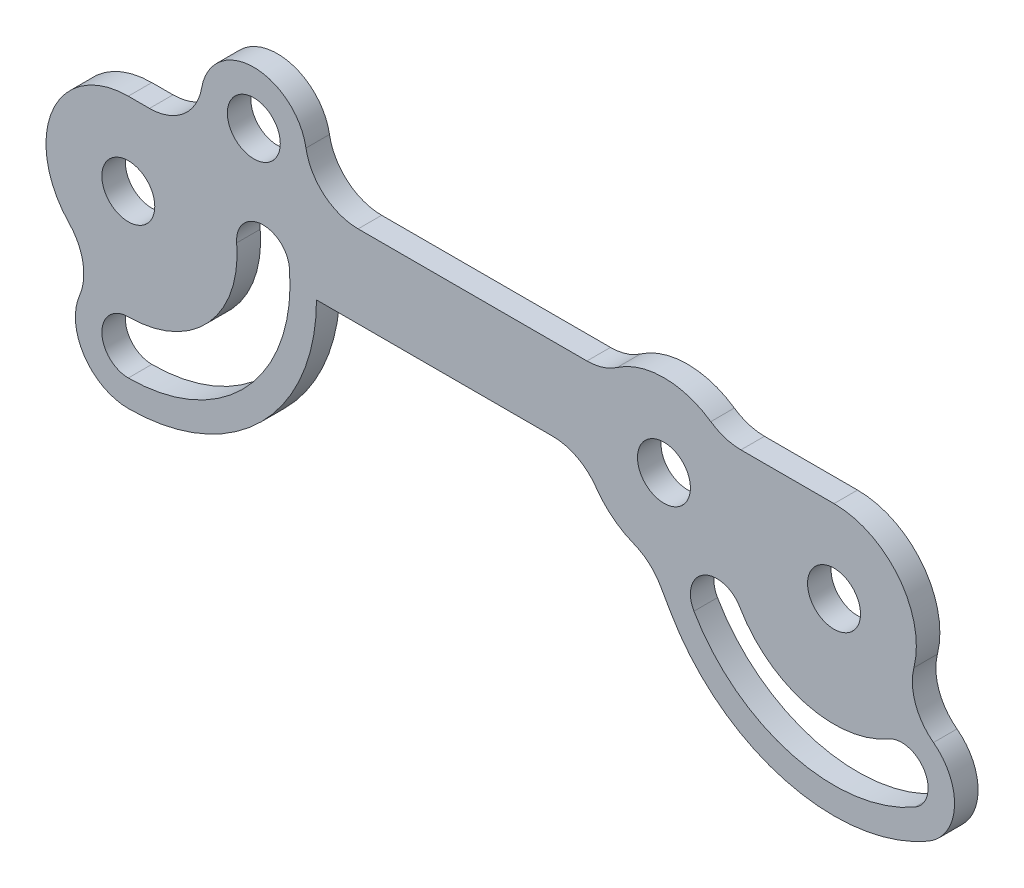
SolidWorks part; units mm, degrees
ref_plane "Front Plane" through (0, 0, 0) normal (0, 0, 1) x (1, 0, 0)
ref_plane "Top Plane" through (0, 0, 0) normal (0, 1, 0) x (1, 0, 0)
ref_plane "Right Plane" through (0, 0, 0) normal (1, 0, 0) x (0, 0, -1)
sketch "Sketch1" plane through (0, 0, 0) normal (0, 0, 1) x (1, 0, 0)
  line L0 (5.5562, 0) -> (42.0688, 0)
  line L1 (0, 5.5562) -> (47.625, 5.5562)
  line L2 (0, 5.5562) -> (0, -5.5562) construction
  line L3 (0, -5.5562) -> (47.625, -5.5562) construction
  line L4 (47.625, 5.5562) -> (47.625, -5.5562) construction
  line L5 (0, 5.5562) -> (47.625, 5.5562) construction
  line L9 (36.6265, -6.35) -> (33.0546, -0.1633)
  line L10 (36.6265, -6.35) -> (39.7198, -4.5641) construction
  line L11 (0, 0) -> (9.0934, 0.7956) construction
  line L12 (9.0934, 0.7956) -> (8.4708, 7.9121) construction
  line L13 (47.625, 0) -> (52.1891, -7.9052) construction
  line L14 (52.1891, -7.9052) -> (53.082, -9.4519) construction
  line L15 (47.625, 0) -> (47.625, -9.1281) construction
  line L16 (47.625, 0) -> (39.7198, -4.5641) construction
  line L17 (39.7198, -4.5641) -> (36.1479, 1.6226) construction
  line L18 (33.0546, -0.1633) -> (32.9603, 0)
  circle A0 centre (0, 0) radius 5.5562 construction
  circle A1 centre (47.625, 0) radius 5.5562 construction
  arc A2 (0, 5.5562) -> (0, -5.5562) centre (0, 0) ccw
  arc A3 (47.625, -5.5562) -> (47.625, 5.5562) centre (47.625, 0) ccw
  circle A4 centre (0, 0) radius 1.7859
  circle A5 centre (47.625, 0) radius 1.7859
  arc A6 (0, -5.5562) -> (5.5562, 0) centre (0, 0) ccw
  arc A7 (42.0688, 0) -> (47.625, -5.5562) centre (47.625, 0) ccw
  circle A16 centre (0, -9.1281) radius 1.7859
  circle A20 centre (0, -9.1281) radius 3.5719
  circle A21 centre (9.0934, 0.7956) radius 1.7859
  circle A22 centre (9.0934, 0.7956) radius 3.5719 construction
  circle A23 centre (47.625, 0) radius 9.1281 construction
  circle A25 centre (0, 0) radius 9.1281 construction
  circle A40 centre (8.4708, 7.9121) radius 1.7859
  circle A41 centre (8.4708, 7.9121) radius 3.5719
  circle A42 centre (39.7198, -4.5641) radius 3.5719
  circle A44 centre (36.1479, 1.6226) radius 3.5719 construction
  circle A46 centre (36.1479, 1.6226) radius 1.7859
  circle A47 centre (39.7198, -4.5641) radius 1.7859
  circle A49 centre (52.1891, -7.9052) radius 3.5719
  circle A50 centre (52.1891, -7.9052) radius 1.7859
  arc A51 (51.2961, -6.3585) -> (41.2665, -3.6711) centre (47.625, 0) cw
  arc A53 (53.082, -9.4519) -> (38.1731, -5.457) centre (47.625, 0) cw
  arc A54 (53.975, -10.9985) -> (36.6265, -6.35) centre (47.625, 0) cw
  arc A55 (7.3142, 0.6399) -> (0, -7.3422) centre (0, 0) cw
  arc A56 (0, -10.9141) -> (10.8725, 0.9512) centre (0, 0) ccw
  arc A57 (0, -12.7) -> (12.6517, 1.1069) centre (0, 0) ccw
  circle A59 centre (36.1479, 1.6226) radius 5.5562
  dimension "D1" = 47.625
  dimension "D2" = 11.1125
  dimension "D3" = 3.5719
  dimension "D6" = 95
  dimension "D7" = 30
  dimension "D8" = 60
  dimension "D4" = 7.1437
extrude "Boss-Extrude1" add sketch "Sketch1" along normal blind 1.5875
fillet "Fillet1" radius 3.5719 8 edges at (50.4031, -4.8119, 0.7937) (5.786, 5.5562, 0.7937) (11.1556, 5.5562, 0.7937) (0, -5.5562, 0.7937) (35.1826, -3.8491, 0.7937) (30.8339, 0, 0.7937) (32.2239, 5.5562, 0.7937) (40.072, 5.5562, 0.7937)
